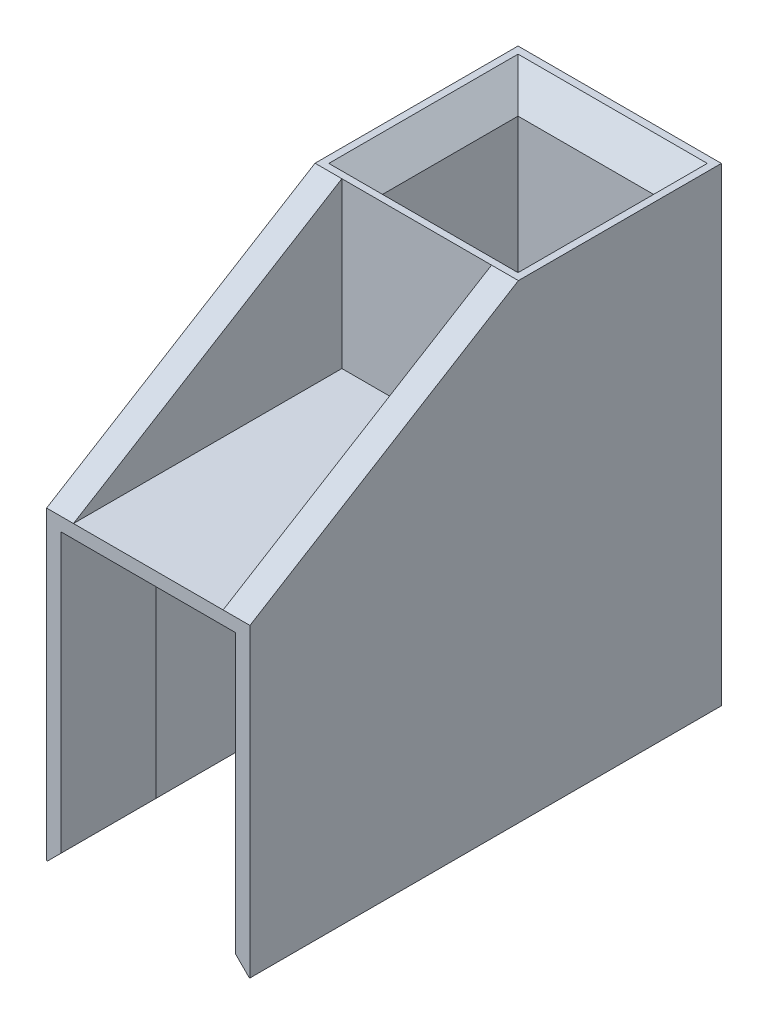
SolidWorks part; units mm, degrees
ref_plane "Alzado" through (0, 0, 0) normal (0, 0, 1) x (1, 0, 0)
ref_plane "Planta" through (0, 0, 0) normal (0, 1, 0) x (1, 0, 0)
ref_plane "Vista lateral" through (0, 0, 0) normal (1, 0, 0) x (0, 0, -1)
sketch "Croquis2" plane through (0, 0, 0) normal (0, 0, 1) x (1, 0, 0)
  line L1 (-15.15, 50) -> (15.15, 50)
  line L2 (-15.15, 50) -> (-15.15, -20)
  line L3 (-15.15, -20) -> (15.15, -20)
  line L4 (15.15, 50) -> (15.15, -20)
  point P0 (0, 50)
  dimension "D1" = 70
  dimension "D2" = 30.3
  dimension "D3" = 20
extrude "Saliente-Extruir2" add sketch "Croquis2" against normal blind 5
sketch "Croquis3" plane through (0, 0, 0) normal (0, 1, 0) x (1, 0, 0)
  line L0 (-15.15, 5) -> (-15.15, 30.25)
  line L1 (-15.15, 30.25) -> (15.15, 30.25)
  line L2 (15.15, 30.25) -> (15.15, 5)
  line L3 (-10.1, 5) -> (-10.1, 25.2)
  line L4 (15.15, 5) -> (-15.15, 5) construction
  line L5 (-10.1, 25.2) -> (10.1, 25.2)
  line L6 (10.1, 25.2) -> (10.1, 5)
  line L7 (0, 25.2) -> (0, 30.25) construction
  line L8 (-10.1, 15.1) -> (-15.15, 15.1) construction
  line L9 (10.1, 15.1) -> (15.15, 15.1) construction
  line L10 (-15.15, 5) -> (15.15, 5)
  line L11 (-10.1, 5) -> (10.1, 5)
  dimension "D1" = 20.2
extrude "Saliente-Extruir3" add sketch "Croquis3" along normal up to surface (70 mm away) from surface at -20 contours L0 L10 L3 L5 L6 L2 L1 up to face at (0, 50, -2.5) starting at face at (0, -20, -2.5)
sketch "Croquis4" plane through (0, 0, 0) normal (0, 1, 0) x (1, 0, 0)
  line L0 (10.1, 5) -> (-10.1, 5) construction
  line L1 (-10.1, 25.2) -> (10.1, 25.2)
  line L2 (-10.1, 25.2) -> (-10.1, 5)
  line L3 (-10.1, 5) -> (10.1, 5)
  line L4 (10.1, 25.2) -> (10.1, 5)
  line L6 (-10.1, 25.2) -> (-10.1, 5) construction
extrude "Saliente-Extruir4" add sketch "Croquis4" along normal blind 4 from surface at -20 starting at face at (0, -20, -15.1)
chamfer "Chaflán4" distance 4 angle 45 4 edges at (0, 50, -5) (10.1, 50, -15.1) (0, 50, -25.2) (-10.1, 50, -15.1)
sketch "Croquis6" plane through (0, 0, 0) normal (0, 0, 1) x (1, 0, 0)
  line L0 (-15.15, 50) -> (-15.15, -20) construction
  line L1 (-15.15, 25.5) -> (15.15, 25.5)
  line L2 (-15.15, 25.5) -> (-15.15, 20.5)
  line L3 (-15.15, 20.5) -> (15.15, 20.5)
  line L4 (15.15, 25.5) -> (15.15, 20.5)
  line L5 (15.15, -20) -> (15.15, 50) construction
  line L6 (-15.15, -20) -> (15.15, -20) construction
  line L8 (-15.15, -20) -> (-10.025, -20)
  line L9 (-15.15, -20) -> (-15.15, 20.5)
  line L10 (-15.15, 20.5) -> (-10.025, 20.5)
  line L11 (-10.025, -20) -> (-10.025, 20.5)
  line L12 (15.15, -20) -> (10.025, -20)
  line L13 (15.15, -20) -> (15.15, 20.5)
  line L14 (15.15, 20.5) -> (10.025, 20.5)
  line L15 (10.025, -20) -> (10.025, 20.5)
  dimension "D1" = 5
  dimension "D2" = 40.5
  dimension "D3" = 20.05
extrude "Saliente-Extruir6" add sketch "Croquis6" along normal blind 40 from surface at 0 contours L4 L1 L2 L3 | L8 L11 L3 L9 | L15 L12 L13 L3 starting at face at (0, 15, 0)
sketch "Croquis7" plane through (0, 0, 0) normal (1, 0, 0) x (0, 0, -1)
  line L0 (-40, 25.5) -> (0, 50)
  line L1 (0, 50) -> (0, 25.5)
  line L2 (-40, -20) -> (-40, 25.5) construction
  line L3 (0, 25.5) -> (-40, 25.5)
  line L4 (0, 25.5) -> (0, 50) construction
  line L6 (-40, 25.5) -> (0, 25.5) construction
extrude "Saliente-Extruir7" add sketch "Croquis7" along normal up to surface (30.3 mm away) from surface at -15.15 up to face at (15.15, 18.5, 3.25) starting at face at (-15.15, 18.5, 3.25)
sketch "Croquis8" plane through (0, 0, 0) normal (0, 0, 1) x (1, 0, 0)
  line L0 (15.15, 50) -> (-15.15, 50) construction
  line L1 (-11.15, 50) -> (11.15, 50)
  line L2 (-11.15, 50) -> (-11.15, 25.5)
  line L3 (-11.15, 25.5) -> (11.15, 25.5)
  line L4 (11.15, 50) -> (11.15, 25.5)
  line L6 (15.15, 25.5) -> (15.15, 50) construction
  line L7 (15.15, 25.5) -> (-15.15, 25.5) construction
  point P8 (0, 50)
  dimension "D1" = 4
extrude "Cortar-Extruir1" cut sketch "Croquis8" along normal blind 40
chamfer "Chaflán7" distance 3 angle 75 3 edges at (-10.025, 0.25, 40) (10.025, 0.25, 40) (0, 20.5, 40)
sketch "Croquis10" plane through (0, 0, 0) normal (0, 0, 1) x (1, 0, 0)
  line L0 (8.4263, 13.5517) -> (8.4263, 15.818)
  line L1 (8.4263, 15.818) -> (7.1073, 15.818)
  line L2 (7.1073, 15.818) -> (4.7887, 13.4995)
  line L3 (4.7887, 13.4995) -> (4.7887, 7.5308)
  line L4 (4.7887, 7.5308) -> (6.7347, 5.5847)
  line L5 (6.7347, 5.5847) -> (8.423, 5.5847)
  line L6 (8.4967, 5.5847) -> (8.4967, 7.372)
  line L7 (8.4967, 7.372) -> (10.3002, 5.5756)
  line L9 (10.3002, 15.4256) -> (8.5002, 13.6256)
  line L10 (0, 20.5) -> (0, 0.5)
  line L11 (10.025, 20.5) -> (-10.025, 20.5) construction
  line L12 (8.5002, 13.6256) -> (8.4263, 13.5517)
  line L13 (8.423, 5.5847) -> (8.4967, 5.5847)
  line L14 (10.3002, 15.4256) -> (10.3002, 5.5756)
  line L15 (-8.4967, 7.372) -> (-10.3002, 5.5756)
  line L16 (10.025, 0.5) -> (-10.025, 0.5)
  line L17 (-10.025, 20.5) -> (-10.025, -20) construction
  line L18 (-8.4967, 5.5847) -> (-8.4967, 7.372)
  line L19 (-8.423, 5.5847) -> (-8.4967, 5.5847)
  line L20 (-6.7347, 5.5847) -> (-8.423, 5.5847)
  line L21 (-4.7887, 7.5308) -> (-6.7347, 5.5847)
  line L22 (-4.7887, 13.4995) -> (-4.7887, 7.5308)
  line L23 (-7.1073, 15.818) -> (-4.7887, 13.4995)
  line L24 (-8.4263, 15.818) -> (-7.1073, 15.818)
  line L25 (-10.3002, 15.4256) -> (-10.3002, 5.5756)
  line L26 (-8.4263, 13.5517) -> (-8.4263, 15.818)
  line L27 (-8.5002, 13.6256) -> (-8.4263, 13.5517)
  line L28 (-10.3002, 15.4256) -> (-8.5002, 13.6256)
  line L29 (7.1073, -14.818) -> (4.7887, -12.4995)
  line L30 (8.4263, -14.818) -> (7.1073, -14.818)
  line L31 (4.7887, -12.4995) -> (4.7887, -6.5308)
  line L32 (4.7887, -6.5308) -> (6.7347, -4.5847)
  line L33 (8.423, -4.5847) -> (8.4967, -4.5847)
  line L34 (6.7347, -4.5847) -> (8.423, -4.5847)
  line L35 (8.4967, -4.5847) -> (8.4967, -6.372)
  line L36 (8.4967, -6.372) -> (10.3002, -4.5756)
  line L37 (10.3002, -14.4256) -> (10.3002, -4.5756)
  line L38 (8.5002, -12.6256) -> (8.4263, -12.5517)
  line L39 (8.4263, -12.5517) -> (8.4263, -14.818)
  line L40 (10.3002, -14.4256) -> (8.5002, -12.6256)
  line L41 (-8.4967, -6.372) -> (-10.3002, -4.5756)
  line L42 (-8.4967, -4.5847) -> (-8.4967, -6.372)
  line L43 (-8.423, -4.5847) -> (-8.4967, -4.5847)
  line L44 (-6.7347, -4.5847) -> (-8.423, -4.5847)
  line L45 (-4.7887, -6.5308) -> (-6.7347, -4.5847)
  line L46 (-10.3002, -14.4256) -> (-10.3002, -4.5756)
  line L47 (-8.5002, -12.6256) -> (-8.4263, -12.5517)
  line L48 (-10.3002, -14.4256) -> (-8.5002, -12.6256)
  line L49 (-8.4263, -12.5517) -> (-8.4263, -14.818)
  line L50 (-4.7887, -12.4995) -> (-4.7887, -6.5308)
  line L51 (-7.1073, -14.818) -> (-4.7887, -12.4995)
  line L52 (-8.4263, -14.818) -> (-7.1073, -14.818)
  point P17 (10.3, 10.5007)
  point P25 (0, 0.5)
  dimension "D1" = 20
sketch "Croquis12" plane through (0, 0, 0) normal (0, 0, 1) x (1, 0, 0)
sketch "Croquis13" plane through (0, -16, 0) normal (0, 1, 0) x (1, 0, 0)
  line L0 (0, 25.2) -> (0, 5) construction
  line L1 (-10.1, 25.2) -> (10.1, 25.2) construction
  line L2 (-10.1, 5) -> (10.1, 5) construction
  line L3 (-10.1, 15.1) -> (10.1, 15.1) construction
  line L4 (-10.1, 25.2) -> (-10.1, 5) construction
  line L5 (10.1, 25.2) -> (10.1, 5) construction
  circle A0 centre (0, 15.1) radius 2.1267
sketch "Croquis15" plane through (0, 0, 0) normal (0, 0, 1) x (1, 0, 0)
  line L0 (-10, 20.2) -> (-10, 0.2)
  line L2 (-10, 20.2) -> (10, 20.2)
  line L3 (-10, 0.2) -> (10, 0.2)
  line L4 (10, 0.2) -> (10, 20.2)
  line L5 (0, 20.2) -> (0, 0.2) construction
  line L6 (-10, 10.2) -> (10, 10.2) construction
  circle A0 centre (0, 10.2) radius 0.9234
  point P8 (0, 20.2)
sketch "Croquis16" plane through (0, 0, 0) normal (0, 0, 1) x (1, 0, 0)
  line L0 (8.1, 13.0875) -> (10.3, 15.2875)
  line L1 (8.2, 13.3289) -> (10, 15.1289) construction
  line L2 (8.1, 15.821) -> (8.1, 13.0875)
  line L3 (8.2, 15.921) -> (8.2, 13.3289) construction
  line L4 (6.8231, 15.821) -> (8.1, 15.821)
  line L5 (6.7816, 15.921) -> (8.2, 15.921) construction
  line L6 (6.8231, 15.821) -> (4.3886, 13.3865)
  line L7 (4.2886, 13.4279) -> (6.7816, 15.921) construction
  line L8 (4.3886, 13.3865) -> (4.3886, 7.0547)
  line L9 (4.2886, 7.0132) -> (4.2886, 13.4279) construction
  line L10 (4.3886, 7.0547) -> (6.4223, 5.021)
  line L11 (4.2886, 7.0132) -> (6.3808, 4.921) construction
  line L12 (6.4223, 5.021) -> (8.1, 5.021)
  line L13 (6.3808, 4.921) -> (8.2, 4.921) construction
  line L14 (8.1, 7.3203) -> (8.1, 5.021)
  line L15 (8.2, 4.921) -> (8.2, 7.0789) construction
  line L16 (-3.1865, 14.5886) -> (3.1865, 14.5886)
  line L17 (8.1, 7.3203) -> (10.3, 5.1203)
  line L18 (8.2, 7.0789) -> (10, 5.2789) construction
  line L21 (0, 20.5) -> (0, -20) construction
  line L24 (-10.3, 5.1203) -> (-10.3, 15.2875)
  line L25 (-8.1, 7.3203) -> (-10.3, 5.1203)
  line L26 (-8.1, 7.3203) -> (-8.1, 5.021)
  line L27 (-6.4223, 5.021) -> (-8.1, 5.021)
  line L28 (-4.3886, 7.0547) -> (-6.4223, 5.021)
  line L29 (-4.3886, 13.3865) -> (-4.3886, 7.0547)
  line L30 (-6.8231, 15.821) -> (-4.3886, 13.3865)
  line L31 (-6.8231, 15.821) -> (-8.1, 15.821)
  line L32 (-8.1, 15.821) -> (-8.1, 13.0875)
  line L33 (-8.1, 13.0875) -> (-10.3, 15.2875)
  line L34 (3.2279, 14.4886) -> (-3.2279, 14.4886) construction
  line L35 (3.1865, 14.5886) -> (5.621, 17.0231)
  line L36 (3.2279, 14.4886) -> (5.721, 16.9816) construction
  line L37 (5.621, 18.3) -> (5.621, 17.0231)
  line L38 (5.721, 18.4) -> (5.721, 16.9816) construction
  line L39 (2.8875, 18.3) -> (5.621, 18.3)
  line L40 (3.1289, 18.4) -> (5.721, 18.4) construction
  line L41 (2.8875, 18.3) -> (5.0875, 20.5)
  line L42 (4.9289, 20.2) -> (3.1289, 18.4) construction
  line L43 (-5.0875, 20.5) -> (5.0875, 20.5)
  line L44 (-5.621, 17.0231) -> (-3.1865, 14.5886)
  line L45 (-3.2279, 14.4886) -> (-5.721, 16.9816) construction
  line L46 (-5.621, 18.3) -> (-5.621, 16.836)
  line L47 (-5.721, 18.4) -> (-5.721, 16.9816) construction
  line L48 (-5.621, 18.3) -> (-2.8875, 18.3)
  line L49 (-3.1289, 18.4) -> (-5.721, 18.4) construction
  line L50 (-5.0875, 20.5) -> (-2.8875, 18.3)
  line L51 (-4.9289, 20.2) -> (-3.1289, 18.4) construction
  line L52 (10.3, 15.2875) -> (10.3, 5.1203)
  line L55 (-7.2144, 0.2) -> (51.7819, 0.2) construction
  line L64 (-8.1, -12.6875) -> (-10.3, -14.8875)
  line L65 (-8.1, -15.421) -> (-8.1, -12.6875)
  line L66 (-6.8231, -15.421) -> (-8.1, -15.421)
  line L67 (-6.8231, -15.421) -> (-4.3886, -12.9865)
  line L68 (-4.3886, -12.9865) -> (-4.3886, -6.6547)
  line L69 (-4.3886, -6.6547) -> (-6.4223, -4.621)
  line L70 (-6.4223, -4.621) -> (-8.1, -4.621)
  line L71 (-8.1, -6.9203) -> (-8.1, -4.621)
  line L72 (-8.1, -6.9203) -> (-10.3, -4.7203)
  line L73 (-10.3, -4.7203) -> (-10.3, -14.8875)
  line L74 (10.3, -4.7203) -> (10.3, -14.8875)
  line L75 (8.1, -6.9203) -> (10.3, -4.7203)
  line L77 (8.1, -6.9203) -> (8.1, -4.621)
  line L78 (6.4223, -4.621) -> (8.1, -4.621)
  line L79 (4.3886, -6.6547) -> (6.4223, -4.621)
  line L80 (4.3886, -12.9865) -> (4.3886, -6.6547)
  line L81 (6.8231, -15.421) -> (4.3886, -12.9865)
  line L82 (6.8231, -15.421) -> (8.1, -15.421)
  line L83 (8.1, -15.421) -> (8.1, -12.6875)
  line L84 (8.1, -12.6875) -> (10.3, -14.8875)
  point P3 (9.2, 14.1875)
  point P8 (8.1, 14.4542)
  point P13 (7.4615, 15.821)
  point P18 (5.6058, 14.6037)
  point P23 (4.3886, 10.2206)
  point P28 (5.4054, 6.0378)
  point P33 (7.2611, 5.021)
  point P38 (8.1, 6.1706)
  point P45 (9.2, 6.2203)
  point P55 (-9.2, 6.2203)
  point P56 (-8.1, 6.1706)
  point P57 (-7.2611, 5.021)
  point P58 (-5.4054, 6.0378)
  point P59 (-4.3886, 10.2206)
  point P60 (-5.6058, 14.6037)
  point P61 (-7.4615, 15.821)
  point P62 (-8.1, 14.4542)
  point P63 (-9.2, 14.1875)
  point P67 (0, 14.5886)
  point P72 (4.4037, 15.8058)
  point P77 (5.621, 17.6615)
  point P82 (4.2542, 18.3)
  point P87 (3.9875, 19.4)
  point P95 (-4.4037, 15.8058)
  point P97 (-5.621, 17.568)
  point P102 (-4.2542, 18.3)
  point P107 (-3.9875, 19.4)
  point P146 (-9.2, -13.7875)
  point P147 (-8.1, -14.0542)
  point P148 (-7.4615, -15.421)
  point P149 (-5.6058, -14.2037)
  point P150 (-4.3886, -9.8206)
  point P151 (-5.4054, -5.6378)
  point P152 (-7.2611, -4.621)
  point P153 (-8.1, -5.7706)
  point P154 (-9.2, -5.8203)
  point P155 (9.2, -5.8203)
  point P156 (8.1, -5.7706)
  point P157 (7.2611, -4.621)
  point P158 (5.4054, -5.6378)
  point P159 (4.3886, -9.8206)
  point P160 (5.6058, -14.2037)
  point P161 (7.4615, -15.421)
  point P162 (8.1, -14.0542)
  point P163 (9.2, -13.7875)
  dimension "D1" = 0.1
  dimension "D2" = 0.1
  dimension "D3" = 0.1
  dimension "D4" = 0.1
  dimension "D5" = 0.1
  dimension "D6" = 0.1
  dimension "D7" = 0.1
  dimension "D8" = 0.1
  dimension "D10" = 0.1
  dimension "D11" = 0.1
  dimension "D12" = 0.1
  dimension "D13" = 0.1
  dimension "D14" = 0.1
  dimension "D15" = 0.1
  dimension "D16" = 0.1
  dimension "D17" = 0.1
sketch "Croquis17" plane through (0, -16, 0) normal (0, 1, 0) x (1, 0, 0)
  line L0 (-8.25, 17.6) -> (-10.1, 17.6)
  line L1 (-8.25, 17.6) -> (-8.25, 20.6397)
  line L2 (-8.25, 20.6397) -> (-7.2424, 20.6397)
  line L3 (-7.2424, 20.6397) -> (-3.85, 17.3867)
  line L4 (-3.85, 17.3867) -> (-3.85, 12.8133)
  line L5 (-3.85, 12.8133) -> (-7.2424, 9.5603)
  line L6 (-8.25, 9.5603) -> (-7.2424, 9.5603)
  line L7 (-8.25, 12.6) -> (-8.25, 9.5603)
  line L8 (-8.25, 12.6) -> (-10.1, 12.6)
  line L9 (-2.5, 6.85) -> (-2.5, 5)
  line L10 (-2.5, 6.85) -> (-5.5397, 6.85)
  line L11 (-5.5397, 6.85) -> (-5.5397, 7.6076)
  line L12 (-5.5397, 7.6076) -> (-2.2867, 11)
  line L13 (-2.2867, 11) -> (2.2867, 11)
  line L14 (2.2867, 11) -> (5.5397, 7.6076)
  line L15 (5.5397, 6.85) -> (5.5397, 7.6076)
  line L16 (2.5, 6.85) -> (5.5397, 6.85)
  line L17 (2.5, 6.85) -> (2.5, 5)
  line L18 (8.25, 12.6) -> (10.1, 12.6)
  line L19 (8.25, 12.6) -> (8.25, 9.5603)
  line L20 (8.25, 9.5603) -> (7.2424, 9.5603)
  line L21 (3.85, 12.8133) -> (7.2424, 9.5603)
  line L22 (3.85, 17.3867) -> (3.85, 12.8133)
  line L23 (7.2424, 20.6397) -> (3.85, 17.3867)
  line L24 (8.25, 20.6397) -> (7.2424, 20.6397)
  line L25 (8.25, 17.6) -> (8.25, 20.6397)
  line L26 (8.25, 17.6) -> (10.1, 17.6)
  line L27 (5.5397, 23.35) -> (5.5397, 22.5924)
  line L28 (2.5, 23.35) -> (5.5397, 23.35)
  line L29 (2.5, 23.35) -> (2.5, 25.2)
  line L30 (2.2867, 19.2) -> (5.5397, 22.5924)
  line L31 (-2.2867, 19.2) -> (2.2867, 19.2)
  line L32 (-5.5397, 22.5924) -> (-2.2867, 19.2)
  line L33 (-5.5397, 23.35) -> (-5.5397, 22.5924)
  line L34 (-2.5, 23.35) -> (-5.5397, 23.35)
  line L35 (-2.5, 23.35) -> (-2.5, 25.2)
  line L36 (-10.1, 25.2) -> (-10.1, 17.6)
  line L37 (-10.1, 5) -> (-10.1, 12.6)
  line L38 (-2.5, 5) -> (-10.1, 5)
  line L39 (10.1, 5) -> (2.5, 5)
  line L40 (10.1, 12.6) -> (10.1, 5)
  line L41 (10.1, 25.2) -> (10.1, 17.6)
  line L42 (2.5, 25.2) -> (10.1, 25.2)
  line L43 (-2.5, 25.2) -> (-10.1, 25.2)
  line L44 (-10.1, 17.6) -> (-10.1, 12.6)
  line L45 (-2.5, 5) -> (2.5, 5)
  line L46 (10.1, 12.6) -> (10.1, 17.6)
  line L47 (2.5, 25.2) -> (-2.5, 25.2)
  dimension "D1" = 20.2
  dimension "D2" = 20.2
sketch "Croquis18" plane through (0, 0, 0) normal (0, 0, 1) x (1, 0, 0)
  line L0 (-10.025, 20.5) -> (-10.025, -19.3)
  line L1 (-10.025, 20.5) -> (-10.025, -20) construction
  line L2 (-10.025, 20.5) -> (10.025, 20.5)
  line L3 (10.025, 20.5) -> (10.025, -19.3)
  line L4 (10.025, -20) -> (10.025, 20.5) construction
  line L5 (10.025, -19.3) -> (-10.025, -19.3)
  line L6 (-10.15, 20.5) -> (-10.15, 13.24)
  line L7 (-10.15, 13.24) -> (-8.3, 13.24)
  line L8 (-8.3, 15.462) -> (-8.3, 13.24)
  line L9 (-8.3, 15.462) -> (-7.2275, 15.462)
  line L10 (-7.2275, 15.462) -> (-4.0258, 13.1381)
  line L11 (-4.0258, 13.1381) -> (-4.0258, 7.742)
  line L12 (-4.0258, 7.742) -> (-7.199, 5.4401)
  line L13 (-7.199, 5.4401) -> (-8.3, 5.4401)
  line L14 (-8.3, 7.34) -> (-8.3, 5.4401)
  line L15 (-8.3, 7.34) -> (-10.15, 7.34)
  line L16 (-10.15, 7.34) -> (-10.15, -6.74)
  line L17 (-8.3, -6.74) -> (-10.15, -6.74)
  line L18 (-8.3, -6.74) -> (-8.3, -4.8401)
  line L19 (-7.199, -4.8401) -> (-8.3, -4.8401)
  line L20 (-4.0258, -7.142) -> (-7.199, -4.8401)
  line L21 (-4.0258, -12.5381) -> (-4.0258, -7.142)
  line L22 (-7.2275, -14.862) -> (-4.0258, -12.5381)
  line L23 (-8.3, -14.862) -> (-7.2275, -14.862)
  line L24 (-8.3, -14.862) -> (-8.3, -12.64)
  line L25 (-10.15, -12.64) -> (-8.3, -12.64)
  line L26 (-10.15, -12.64) -> (-10.15, -19.8)
  line L27 (-10.15, -19.8) -> (10.15, -19.8)
  line L28 (10.15, -19.8) -> (10.15, -12.64)
  line L29 (4.0258, -12.5381) -> (4.0258, -7.142)
  line L30 (7.2275, -14.862) -> (4.0258, -12.5381)
  line L31 (8.3, -14.862) -> (7.2275, -14.862)
  line L32 (8.3, -14.862) -> (8.3, -12.64)
  line L33 (10.15, -12.64) -> (8.3, -12.64)
  line L34 (4.0258, -7.142) -> (7.199, -4.8401)
  line L35 (7.199, -4.8401) -> (8.3, -4.8401)
  line L36 (8.3, -6.74) -> (8.3, -4.8401)
  line L37 (8.3, -6.74) -> (10.15, -6.74)
  line L38 (10.15, -6.74) -> (10.15, 7.34)
  line L39 (7.199, 5.4401) -> (8.3, 5.4401)
  line L40 (8.3, 7.34) -> (8.3, 5.4401)
  line L41 (8.3, 7.34) -> (10.15, 7.34)
  line L42 (4.0258, 7.742) -> (7.199, 5.4401)
  line L43 (4.0258, 13.1381) -> (4.0258, 7.742)
  line L44 (7.2275, 15.462) -> (4.0258, 13.1381)
  line L45 (8.3, 15.462) -> (7.2275, 15.462)
  line L46 (8.3, 15.462) -> (8.3, 13.24)
  line L47 (10.15, 13.24) -> (8.3, 13.24)
  line L48 (10.15, 13.24) -> (10.15, 20.5)
  line L49 (10.15, 20.5) -> (2.95, 20.5)
  line L50 (2.95, 18.75) -> (2.95, 20.5)
  line L51 (2.95, 18.75) -> (5.17, 18.75)
  line L52 (5.17, 18.75) -> (5.17, 17.649)
  line L53 (5.17, 17.649) -> (2.5489, 14.4758)
  line L54 (-2.8472, 14.4758) -> (2.5489, 14.4758)
  line L55 (-5.17, 17.649) -> (-2.8472, 14.4758)
  line L56 (-5.17, 18.65) -> (-5.17, 17.649)
  line L57 (-2.95, 18.65) -> (-5.17, 18.65)
  line L58 (-2.95, 20.5) -> (-2.95, 18.65)
  line L59 (-2.95, 20.5) -> (-10.15, 20.5)
  line L60 (-10.15, 20.5) -> (-10.15, -19.8) construction
  line L61 (-10.15, 20.5) -> (10.15, 20.5) construction
  line L62 (-2.95, 20.5) -> (2.95, 20.5)
  line L63 (10.15, 13.24) -> (10.15, 7.34)
  line L64 (-10.15, 13.24) -> (-10.15, 7.34)
  line L65 (-10.15, -6.74) -> (-10.15, -12.64)
  line L66 (10.15, -6.74) -> (10.15, -12.64)
  point P64 (0, 20.5)
  point P65 (0, 20.5)
  dimension "D1" = 39.8
  dimension "D2" = 20.3
  dimension "D3" = 20.3
  dimension "D4" = 40.3
sketch "Croquis19" plane through (-15.15, 0, 0) normal (-1, 0, 0) x (0, 0, 1)
  line L0 (40, 25.5) -> (-30.25, 25.5)
  line L1 (-30.25, 50) -> (-30.25, -20) construction
  line L2 (-30.25, 25.5) -> (-30.25, 51.6017)
  line L3 (-30.25, 51.6017) -> (38.9778, 50)
  line L4 (38.9778, 50) -> (40, 25.5)
chamfer "Chaflán9" distance 5 angle 45 2 edges at (10.025, -20, 14.4019) (-10.025, -20, 14.4019)
